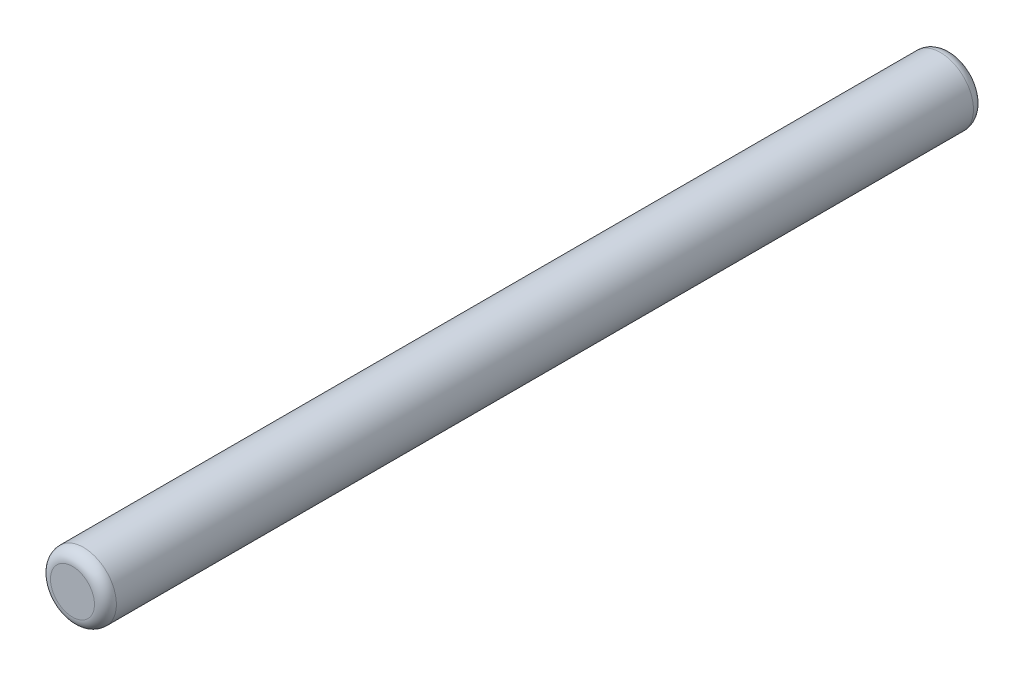
SolidWorks part; units mm, degrees
ref_plane "Plan de face" through (0, 0, 0) normal (0, 0, 1) x (1, 0, 0)
ref_plane "Plan de dessus" through (0, 0, 0) normal (0, 1, 0) x (1, 0, 0)
ref_plane "Plan de droite" through (0, 0, 0) normal (1, 0, 0) x (0, 0, -1)
sketch "Esquisse1" plane through (0, 0, 0) normal (0, 0, 1) x (1, 0, 0)
  circle A0 centre (0, 0) radius 3
  dimension "D1" = 6
extrude "Boss.-Extru.1" add sketch "Esquisse1" along normal blind 80
fillet "Congé1" radius 1 2 edges at (3, 0, 80) (3, 0, 0)
